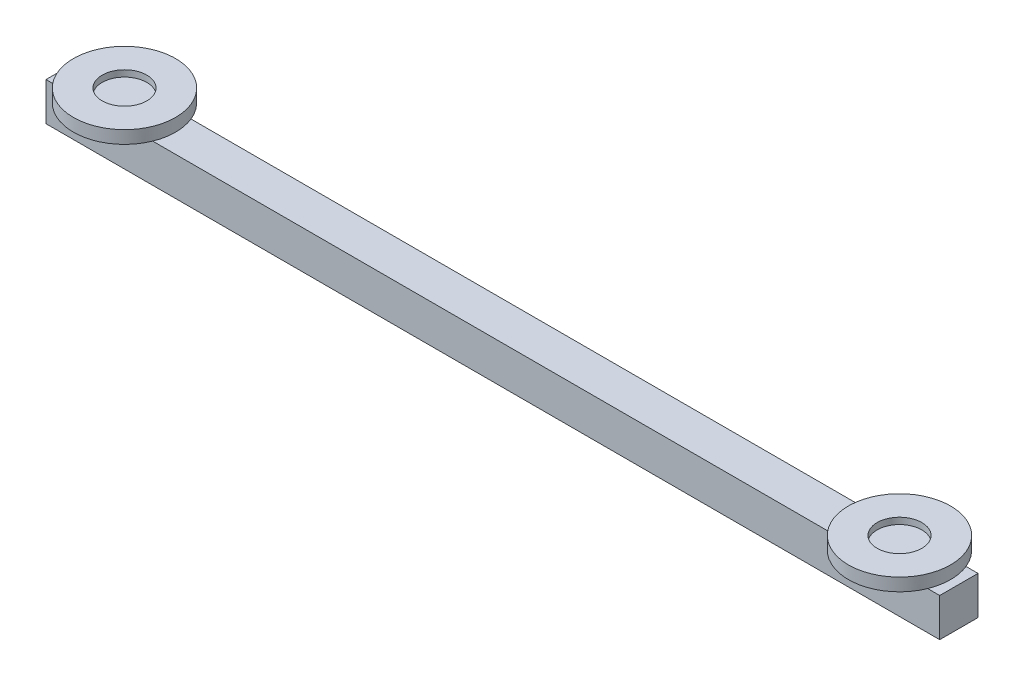
SolidWorks part; units mm, degrees
ref_plane "Front Plane" through (0, 0, 0) normal (0, 0, 1) x (1, 0, 0)
ref_plane "Top Plane" through (0, 0, 0) normal (0, 1, 0) x (1, 0, 0)
ref_plane "Right Plane" through (0, 0, 0) normal (1, 0, 0) x (0, 0, -1)
sketch "Sketch1" plane through (0, 0, 0) normal (1, 0, 0) x (0, 0, -1)
  line L1 (-15, -15) -> (15, -15)
  line L2 (-15, -15) -> (-15, 15)
  line L3 (-15, 15) -> (15, 15)
  line L4 (15, -15) -> (15, 15)
  line L5 (-15, -15) -> (15, 15) construction
  line L6 (-15, 15) -> (15, -15) construction
  point P0 (0, 0)
  dimension "D1" = 30
  dimension "D2" = 30
extrude "Boss-Extrude1" add sketch "Sketch1" along normal mid plane 700
sketch "Sketch2" plane through (0, 15, 0) normal (0, 1, 0) x (1, 0, 0)
  circle A0 centre (303.5145, 0) radius 40
  point P2 (303.5145, 0)
  dimension "D1" = 80
extrude "Boss-Extrude2" add sketch "Sketch2" along normal blind 10
sketch "Sketch3" plane through (0, 25, 0) normal (0, 1, 0) x (1, 0, 0)
  circle A0 centre (303.5145, 0) radius 17.5
  dimension "D1" = 35
extrude "Cut-Extrude1" cut sketch "Sketch3" against normal blind 5
mirror "Mirror1" about plane through (0, 0, 0) normal (1, 0, 0) of "Boss-Extrude2", "Cut-Extrude1"
